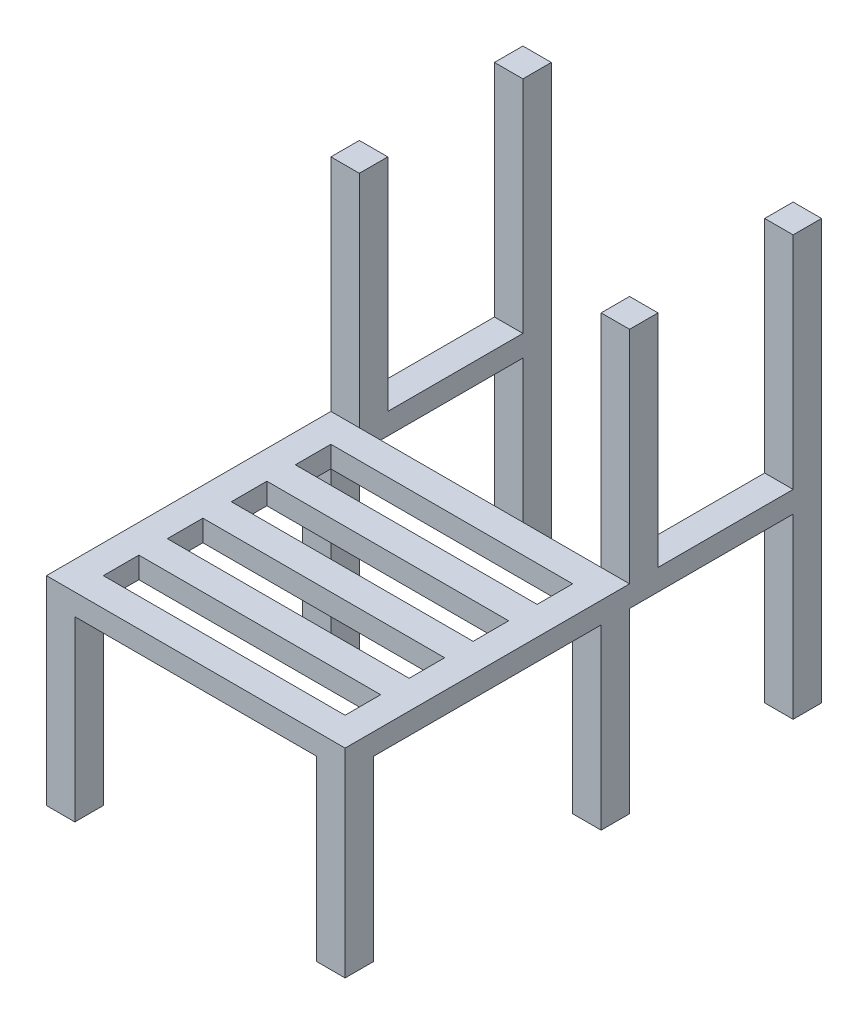
SolidWorks part; units mm, degrees
material "Cast Stainless Steel"
ref_plane "Front Plane" through (0, 0, 0) normal (0, 0, 1) x (1, 0, 0)
ref_plane "Top Plane" through (0, 0, 0) normal (0, 1, 0) x (1, 0, 0)
ref_plane "Right Plane" through (0, 0, 0) normal (1, 0, 0) x (0, 0, -1)
sketch "Sketch1" plane through (0, 0, 0) normal (0, 0, 1) x (1, 0, 0)
  line L0 (190, 0) -> (190, 15) construction
  line L1 (-20, 15) -> (20, 15)
  line L2 (-20, 15) -> (-20, -15)
  line L3 (-20, -15) -> (20, -15)
  line L4 (20, 15) -> (20, -15)
  line L5 (-20, 15) -> (20, -15) construction
  line L6 (-20, -15) -> (20, 15) construction
  line L7 (400, 15) -> (360, -15) construction
  line L8 (400, -15) -> (360, 15) construction
  line L9 (360, 15) -> (360, -15)
  line L10 (400, -15) -> (360, -15)
  line L11 (400, 15) -> (400, -15)
  line L12 (400, 15) -> (360, 15)
  point P0 (0, 0)
  dimension "D1" = 40
  dimension "D2" = 30
  dimension "D3" = 190
extrude "Boss-Extrude1" add sketch "Sketch1" along normal blind 400
sketch "Sketch2" plane through (20, 0, 0) normal (1, 0, 0) x (0, 0, -1)
  line L0 (-400, -15) -> (0, -15) construction
  line L1 (-400, 15) -> (-360, 15)
  line L2 (-400, 15) -> (-400, -15)
  line L3 (-400, -15) -> (-360, -15)
  line L4 (-360, 15) -> (-360, -15)
  line L5 (-400, 15) -> (0, 15) construction
  line L6 (-310, 15) -> (-270, 15)
  line L7 (-310, 15) -> (-310, -15)
  line L8 (-310, -15) -> (-270, -15)
  line L9 (-270, 15) -> (-270, -15)
  line L11 (-130, 15) -> (-90, 15)
  line L12 (-130, 15) -> (-130, -15)
  line L13 (-130, -15) -> (-90, -15)
  line L14 (-90, 15) -> (-90, -15)
  line L15 (-40, 15) -> (0, 15)
  line L16 (-40, 15) -> (-40, -15)
  line L17 (-40, -15) -> (0, -15)
  line L18 (0, 15) -> (0, -15)
  line L19 (-220, 15) -> (-180, 15)
  line L20 (-220, 15) -> (-220, -15)
  line L21 (-220, -15) -> (-180, -15)
  line L22 (-180, 15) -> (-180, -15)
  dimension "D1" = 40
  dimension "D2" = 40
  dimension "D3" = 40
  dimension "D4" = 40
  dimension "D5" = 40
  dimension "D6" = 50
  dimension "D7" = 50
  dimension "D8" = 50
extrude "Boss-Extrude2" add sketch "Sketch2" along normal up to next
sketch "Sketch3" plane through (0, -15, 0) normal (0, -1, 0) x (1, 0, 0)
  line L1 (-20, 400) -> (20, 400)
  line L2 (-20, 400) -> (-20, 360)
  line L3 (-20, 360) -> (20, 360)
  line L4 (20, 400) -> (20, 360)
  line L5 (-20, 0) -> (20, 0)
  line L6 (-20, 0) -> (-20, 40)
  line L7 (-20, 40) -> (20, 40)
  line L8 (20, 0) -> (20, 40)
  line L9 (360, 360) -> (400, 360)
  line L10 (360, 360) -> (360, 400)
  line L11 (360, 400) -> (400, 400)
  line L12 (400, 360) -> (400, 400)
  line L13 (400, 0) -> (360, 0)
  line L14 (400, 0) -> (400, 40)
  line L15 (400, 40) -> (360, 40)
  line L16 (360, 0) -> (360, 40)
extrude "Boss-Extrude3" add sketch "Sketch3" along normal blind 250
sketch "Sketch4" plane through (0, 0, 0) normal (0, 0, -1) x (-1, 0, 0)
  line L1 (-400, 15) -> (-360, 15)
  line L2 (-400, 15) -> (-400, -15)
  line L3 (-400, -15) -> (-360, -15)
  line L4 (-360, 15) -> (-360, -15)
  line L5 (-20, -15) -> (20, -15)
  line L6 (-20, -15) -> (-20, 15)
  line L7 (-20, 15) -> (20, 15)
  line L8 (20, -15) -> (20, 15)
extrude "Boss-Extrude4" add sketch "Sketch4" along normal blind 270
sketch "Sketch5" plane through (0, -15, 0) normal (0, -1, 0) x (1, 0, 0)
  line L0 (-20, -270) -> (-20, 0) construction
  line L1 (20, -270) -> (-20, -270)
  line L2 (20, -270) -> (20, -230)
  line L3 (20, -230) -> (-20, -230)
  line L4 (-20, -270) -> (-20, -230)
  line L5 (360, -270) -> (360, 0) construction
  line L6 (400, -270) -> (360, -270)
  line L7 (400, -270) -> (400, -230)
  line L8 (400, -230) -> (360, -230)
  line L9 (360, -270) -> (360, -230)
  dimension "D1" = 40
extrude "Boss-Extrude5" add sketch "Sketch5" along normal blind 250
sketch "Sketch6" plane through (0, 15, 0) normal (0, 1, 0) x (1, 0, 0)
  line L0 (20, 270) -> (20, 0) construction
  line L1 (-20, 270) -> (20, 270)
  line L2 (-20, 270) -> (-20, 230)
  line L3 (-20, 230) -> (20, 230)
  line L4 (20, 270) -> (20, 230)
  line L5 (400, -400) -> (400, 270) construction
  line L6 (360, 270) -> (400, 270)
  line L7 (360, 270) -> (360, 230)
  line L8 (360, 230) -> (400, 230)
  line L9 (400, 270) -> (400, 230)
  line L10 (-154, 0) -> (154, 0) construction
  line L11 (-20, 0) -> (20, 0)
  line L12 (-20, 0) -> (-20, 40)
  line L13 (-20, 40) -> (20, 40)
  line L14 (20, 0) -> (20, 40)
  line L15 (-20, -400) -> (-20, 270) construction
  line L16 (360, 270) -> (360, 0) construction
  line L17 (400, 0) -> (360, 0)
  line L18 (400, 0) -> (400, 40)
  line L19 (400, 40) -> (360, 40)
  line L20 (360, 0) -> (360, 40)
  dimension "D1" = 40
  dimension "D2" = 40
extrude "Boss-Extrude6" add sketch "Sketch6" along normal blind 310
equation "\"D2@Sketch2\"=\"D1@Sketch2\""
equation "\"D3@Sketch2\"=\"D1@Sketch2\""
equation "\"D4@Sketch2\"=\"D1@Sketch2\""
equation "\"D5@Sketch2\"=\"D1@Sketch2\""
